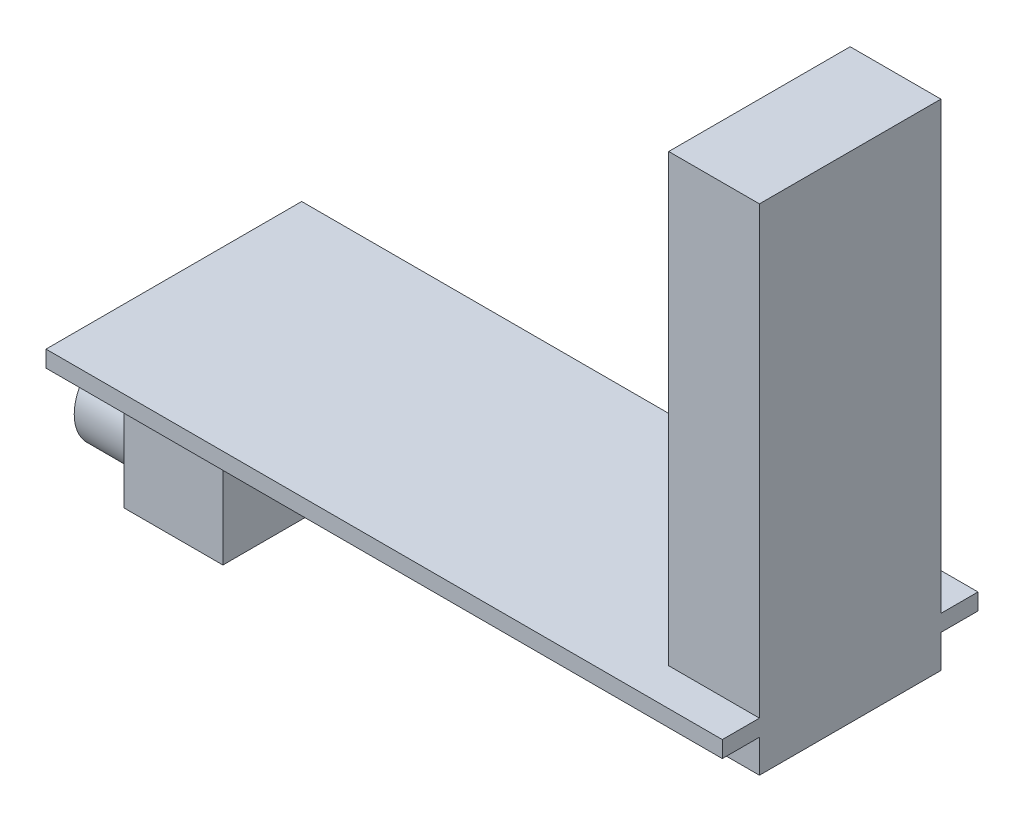
SolidWorks part; units mm, degrees
ref_plane "前视基准面" through (0, 0, 0) normal (0, 0, 1) x (1, 0, 0)
ref_plane "上视基准面" through (0, 0, 0) normal (0, 1, 0) x (1, 0, 0)
ref_plane "右视基准面" through (0, 0, 0) normal (1, 0, 0) x (0, 0, -1)
other "Configuration Table"
sketch "草图1" plane through (0, 0, 0) normal (0, 1, 0) x (1, 0, 0)
  line L1 (-20.5, -7.75) -> (20.5, -7.75)
  line L2 (-20.5, -7.75) -> (-20.5, 7.75)
  line L3 (-20.5, 7.75) -> (20.5, 7.75)
  line L4 (20.5, -7.75) -> (20.5, 7.75)
  line L5 (-20.5, -7.75) -> (20.5, 7.75) construction
  line L6 (-20.5, 7.75) -> (20.5, -7.75) construction
  point P0 (0, 0)
  dimension "D1" = 15.5
  dimension "D2" = 41
extrude "凸台-拉伸1" add sketch "草图1" along normal blind 1
sketch "草图2" plane through (0, 1, 0) normal (0, 1, 0) x (1, 0, 0)
  line L1 (15, -5.5) -> (26, -5.5)
  line L2 (15, -5.5) -> (15, 5.5)
  line L3 (15, 5.5) -> (26, 5.5)
  line L4 (20.5, -7.75) -> (20.5, 7.75)
  line L5 (20.5, 7.75) -> (-20.5, 7.75)
  line L6 (-20.5, 7.75) -> (-20.5, -7.75)
  line L7 (-20.5, -7.75) -> (20.5, -7.75)
  line L8 (20.5, -7.75) -> (20.5, 7.75)
  line L9 (20.5, 7.75) -> (-20.5, 7.75)
  line L10 (-20.5, 7.75) -> (-20.5, -7.75)
  line L11 (-20.5, -7.75) -> (20.5, -7.75)
  line L12 (26, -5.5) -> (26, 5.5)
  line L13 (15, -5.5) -> (26, 5.5) construction
  line L14 (15, 5.5) -> (26, -5.5) construction
  point P2 (20.5, 0)
  line M7 (20.5, -7.75) -> (20.5, 7.75)
  dimension "D2" = 11
  dimension "D3" = 11
  dimension "D1" = 0
extrude "凸台-拉伸2" add sketch "草图2" along normal blind 27 contours L3 L2 L1 M7
sketch "草图3" plane through (0, 0, 0) normal (0, -1, 0) x (1, 0, 0)
  line L4 (20.5, -7.75) -> (20.5, 7.75)
  line L5 (20.5, 7.75) -> (-20.5, 7.75)
  line L6 (-20.5, 7.75) -> (-20.5, -7.75)
  line L7 (-20.5, -7.75) -> (20.5, -7.75)
  line L8 (20.5, -7.75) -> (20.5, 7.75)
  line L9 (20.5, 7.75) -> (-20.5, 7.75)
  line L10 (-20.5, 7.75) -> (-20.5, -7.75)
  line L11 (-20.5, -7.75) -> (20.5, -7.75)
  line L12 (15, -5.5) -> (20.5, -5.5)
  line L13 (15, 5.5) -> (15, -5.5)
  line L14 (20.5, 5.5) -> (15, 5.5)
  line L15 (20.5, -5.5) -> (20.5, 5.5)
  line L16 (15, -5.5) -> (20.5, -5.5)
  line L17 (15, 5.5) -> (15, -5.5)
  line L18 (20.5, 5.5) -> (15, 5.5)
  line L19 (20.5, -5.5) -> (20.5, 5.5)
  dimension "D1" = 0
  dimension "D2" = 0
extrude "凸台-拉伸3" add sketch "草图3" along normal blind 2 contours L8 L18 L17 L16
sketch "草图4" plane through (0, 0, 0) normal (0, -1, 0) x (1, 0, 0)
  line L1 (-26.5, -3.025) -> (-14.5, -3.025)
  line L2 (-26.5, -3.025) -> (-26.5, 3.025)
  line L3 (-26.5, 3.025) -> (-14.5, 3.025)
  line L4 (-14.5, -3.025) -> (-14.5, 3.025)
  line L5 (-26.5, -3.025) -> (-14.5, 3.025) construction
  line L6 (-26.5, 3.025) -> (-14.5, -3.025) construction
  line L8 (20.5, -5.5) -> (15, -5.5)
  line L9 (15, -5.5) -> (15, 5.5)
  line L10 (15, 5.5) -> (20.5, 5.5)
  line L11 (20.5, 5.5) -> (20.5, 7.75)
  line L12 (20.5, 7.75) -> (-20.5, 7.75)
  line L13 (-20.5, 7.75) -> (-20.5, -7.75)
  line L14 (-20.5, -7.75) -> (20.5, -7.75)
  line L15 (20.5, -7.75) -> (20.5, -5.5)
  line L16 (20.5, -5.5) -> (15, -5.5)
  line L17 (15, -5.5) -> (15, 5.5)
  line L18 (15, 5.5) -> (20.5, 5.5)
  line L19 (20.5, 5.5) -> (20.5, 7.75)
  line L20 (20.5, 7.75) -> (-20.5, 7.75)
  line L21 (-20.5, 7.75) -> (-20.5, -7.75)
  line L22 (-20.5, -7.75) -> (20.5, -7.75)
  line L23 (20.5, -7.75) -> (20.5, -5.5)
  point P2 (-20.5, 0)
  line M16 (-20.5, 7.75) -> (-20.5, -7.75)
  dimension "D2" = 6.05
  dimension "D3" = 12
  dimension "D1" = 0
extrude "凸台-拉伸4" add sketch "草图4" along normal blind 9.7 contours L1 L4 L3 M16
sketch "草图5" plane through (-20.5, 0, 0) normal (-1, 0, 0) x (0, 0, 1)
  line L0 (0, 1) -> (0, -6.6792)
  line L8 (-7.75, 0) -> (-3.025, 0)
  line L9 (-3.025, 0) -> (-3.025, -9.7)
  line L10 (-3.025, -9.7) -> (3.025, -9.7)
  line L11 (3.025, -9.7) -> (3.025, 0)
  line L12 (3.025, 0) -> (7.75, 0)
  line L13 (7.75, 0) -> (7.75, 1)
  line L14 (7.75, 1) -> (-7.75, 1)
  line L15 (-7.75, 1) -> (-7.75, 0)
  line L16 (-7.75, 0) -> (-3.025, 0)
  line L17 (-3.025, 0) -> (-3.025, -9.7)
  line L18 (-3.025, -9.7) -> (3.025, -9.7)
  line L19 (3.025, -9.7) -> (3.025, 0)
  line L20 (3.025, 0) -> (7.75, 0)
  line L21 (7.75, 0) -> (7.75, 1)
  line L22 (7.75, 1) -> (-7.75, 1)
  line L23 (-7.75, 1) -> (-7.75, 0)
  circle A0 centre (0, -6.6792) radius 2.64
  dimension "D2" = 5.28
  dimension "D1" = 0
extrude "凸台-拉伸5" add sketch "草图5" along normal blind 3.4
